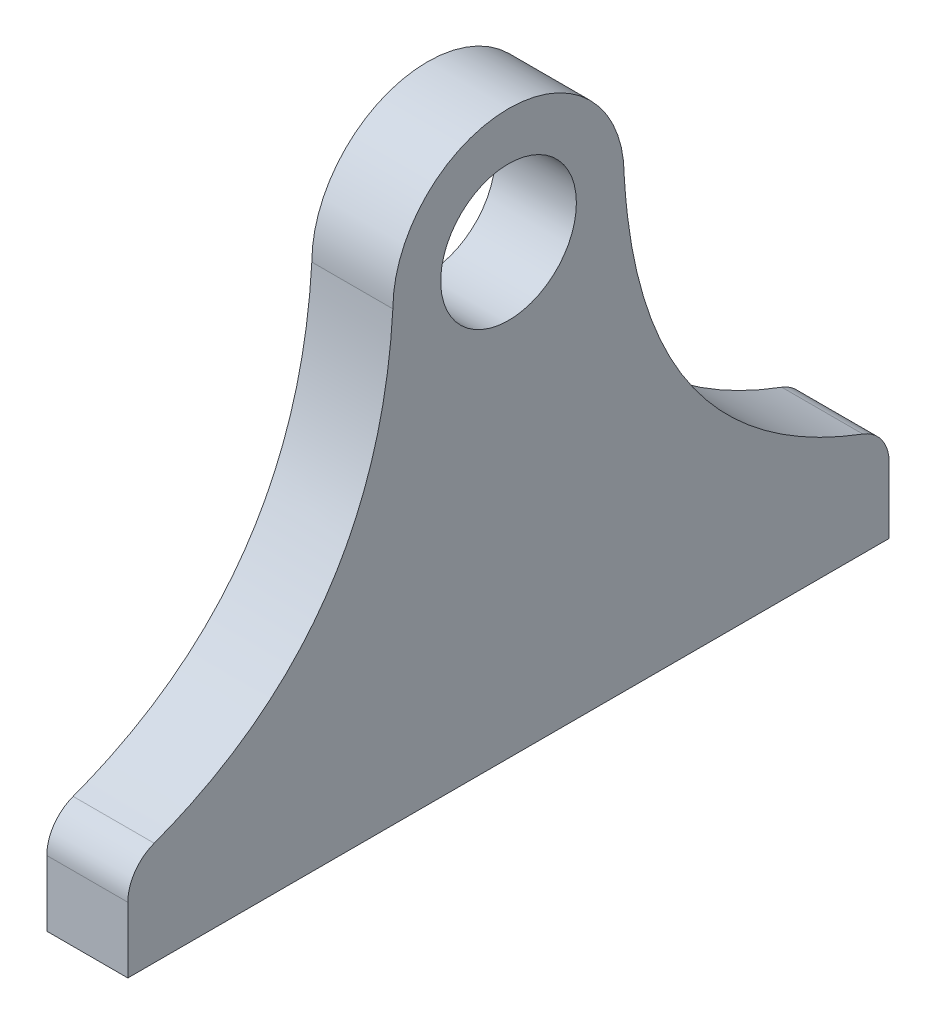
SolidWorks part; units mm, degrees
ref_plane "Front Plane" through (0, 0, 0) normal (0, 0, 1) x (1, 0, 0)
ref_plane "Top Plane" through (0, 0, 0) normal (0, 1, 0) x (1, 0, 0)
ref_plane "Right Plane" through (0, 0, 0) normal (1, 0, 0) x (0, 0, -1)
sketch "Sketch1" plane through (0, 0, 0) normal (1, 0, 0) x (0, 0, -1)
  line L0 (0, -1000) -> (0, 49000) construction
  line L1 (46.9635, -11.6666) -> (-46.9635, -11.6666)
  line L2 (-46.9635, -11.6666) -> (-46.9635, 0)
  line L3 (-46.9635, 0) -> (-14.2674, 0) construction
  line L4 (-14.2674, 0) -> (-14.2674, 43.471) construction
  line L5 (14.2674, 0) -> (14.2674, 43.471) construction
  line L6 (46.9635, 0) -> (14.2674, 0) construction
  line L7 (46.9635, -11.6666) -> (46.9635, 0)
  arc A0 (14.2674, 43.471) -> (-14.2674, 43.471) centre (0, 43.471) ccw
  circle A1 centre (0, 43.471) radius 8.3712
  spline S0 degree 2 poles (-46.9635, 0) (-16.2211, 9.5675) (-14.2674, 43.471) knots 0 0 0 1 1 1
  spline S1 degree 2 poles (46.9635, 0) (16.2211, 9.5675) (14.2674, 43.471) knots 0 0 0 1 1 1
  point P13 (0, -11.6666)
extrude "Boss-Extrude1" add sketch "Sketch1" along normal blind 10
fillet "Fillet1" radius 5 2 edges at (5, 0, 46.9635) (5, 0, -46.9635)
